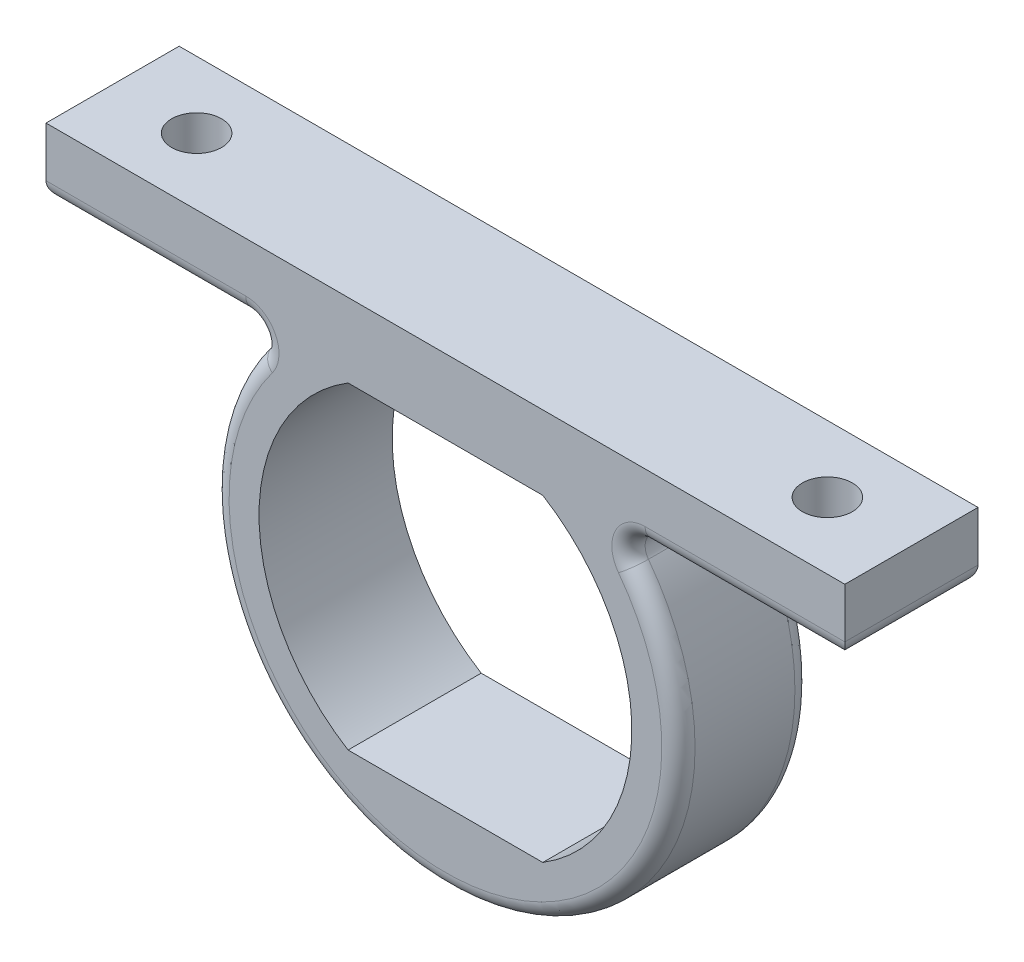
SolidWorks part; units mm, degrees
ref_plane "Alzado" through (0, 0, 0) normal (0, 0, 1) x (1, 0, 0)
ref_plane "Planta" through (0, 0, 0) normal (0, 1, 0) x (1, 0, 0)
ref_plane "Vista lateral" through (0, 0, 0) normal (1, 0, 0) x (0, 0, -1)
sketch "Croquis1" plane through (0, 0, 0) normal (0, 0, 1) x (1, 0, 0)
  line L0 (0, 14) -> (-24, 14)
  line L1 (-24, 14) -> (-24, 10)
  line L2 (-24, 10) -> (-9.798, 10)
  line L3 (0, 14) -> (24, 14)
  line L4 (24, 14) -> (24, 10)
  line L5 (0, -10) -> (0, 10) construction
  line L6 (24, 10) -> (9.798, 10)
  circle A0 centre (0, 0) radius 10
  arc A1 (-9.798, 10) -> (9.798, 10) centre (0, 0) ccw
  dimension "D1" = 20
  dimension "D2" = 48
  dimension "D5" = 24
  dimension "D4" = 4
  dimension "D3" = 14
extrude "Saliente-Extruir1" add sketch "Croquis1" along normal blind 8 contours L4 L6 A1 L2 L1 L0 L3
sketch "Croquis2" plane through (0, 0, 8) normal (0, 0, 1) x (1, 0, 0)
  line L0 (-5.85, 9.5508) -> (5.85, 9.5508)
  line L1 (-5.85, -9.5508) -> (5.85, -9.5508)
  arc A0 (-5.85, 9.5508) -> (-5.85, -9.5508) centre (0, 0) ccw
  arc A1 (5.85, 9.5508) -> (5.85, -9.5508) centre (0, 0) cw
  dimension "D1" = 11.2
  dimension "D2" = 11.7
  dimension "D4" = 11.2
  dimension "D3" = 11.7
extrude "Cortar-Extruir1" cut sketch "Croquis2" against normal through all
fillet "Redondeo1" radius 1 10 edges at (-16.899, 10, 8) (-16.899, 10, 0) (16.899, 10, 8) (16.899, 10, 0) (-9.798, 10, 4) (0, -14, 8) (9.798, 10, 4) (0, -14, 0) (24, 10, 4) (-24, 10, 4)
sketch "Croquis3" plane through (0, 10, 0) normal (0, -1, 0) x (-1, 0, 0)
  line L0 (23, -7) -> (23, -1) construction
  line L2 (12, -7) -> (23, -7) construction
  line L4 (-23, -7) -> (-12, -7) construction
  line L5 (-23, -1) -> (-23, -7) construction
  circle A0 centre (18.9495, -4) radius 1.5
  circle A1 centre (-18.9495, -4) radius 1.5
  dimension "D1" = 3
  dimension "D2" = 3
  dimension "D3" = 4.0505
  dimension "D4" = 3
  dimension "D5" = 3
  dimension "D6" = 4.0505
extrude "Cortar-Extruir2" cut sketch "Croquis3" against normal through all
